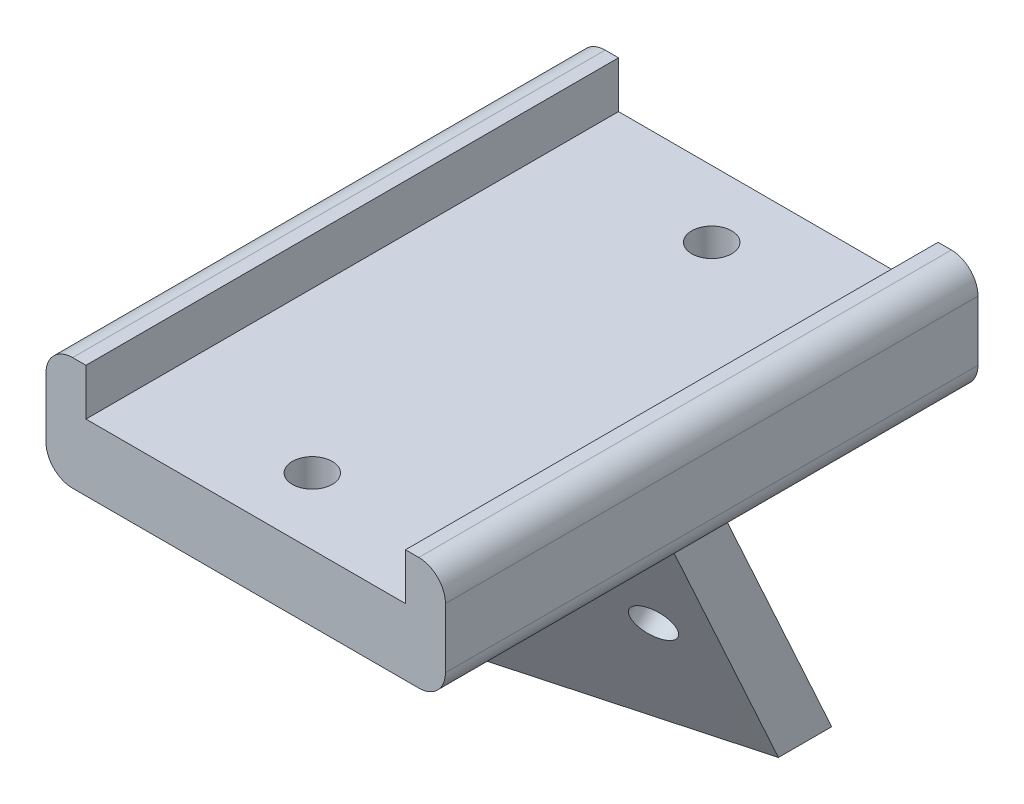
SolidWorks part; units mm, degrees
ref_plane "Front Plane" through (0, 0, 0) normal (0, 0, 1) x (1, 0, 0)
ref_plane "Top Plane" through (0, 0, 0) normal (0, 1, 0) x (1, 0, 0)
ref_plane "Right Plane" through (0, 0, 0) normal (1, 0, 0) x (0, 0, -1)
sketch "Sketch1" plane through (0, 0, 0) normal (0, 1, 0) x (1, 0, 0)
  line L1 (-11, -20) -> (11, -20)
  line L2 (-11, -20) -> (-11, 20)
  line L3 (-11, 20) -> (11, 20)
  line L4 (11, -20) -> (11, 20)
  line L5 (-11, -20) -> (11, 20) construction
  line L6 (-11, 20) -> (11, -20) construction
  circle A0 centre (0, 15) radius 1.5
  circle A1 centre (0, -15) radius 1.5
  point P0 (0, 0)
  dimension "D1" = 30
  dimension "D2" = 15
  dimension "D3" = 3
  dimension "D4" = 3
  dimension "D5" = 40
  dimension "D6" = 22
extrude "Boss-Extrude1" add sketch "Sketch1" along normal blind 5
sketch "Sketch2" plane through (0, 0, 0) normal (0, -1, 0) x (1, 0, 0)
  line L0 (-11, 6) -> (11, 0.1051)
  line L1 (-11, -20) -> (-11, 20) construction
  line L2 (11, 20) -> (11, -20) construction
  line L3 (11, 0.1051) -> (11, -3.8949)
  line L4 (11, -3.8949) -> (-11, 2)
  line L5 (-11, 2) -> (-11, 6)
  dimension "D1" = 4
  dimension "D2" = 4
  dimension "D3" = 105
  dimension "D4" = 14
sketch "Sketch4" plane through (0, 0, -20) normal (0, 0, -1) x (-1, 0, 0)
  line L0 (-11, 5) -> (-12, 5)
  line L1 (-12, 5) -> (-12, 8.5)
  line L2 (-12, 8.5) -> (-15, 8.5)
  line L3 (-15, 8.5) -> (-15, 0)
  line L4 (-15, 0) -> (-11, 0)
  line L5 (-11, 0) -> (-11, 5)
  line L6 (0, 0) -> (0, 5) construction
  line L7 (-11, 0) -> (11, 0) construction
  line L8 (-11, 5) -> (11, 5) construction
  line L9 (11, 0) -> (11, 5)
  line L10 (15, 0) -> (11, 0)
  line L11 (15, 8.5) -> (15, 0)
  line L12 (12, 8.5) -> (15, 8.5)
  line L13 (12, 5) -> (12, 8.5)
  line L14 (11, 5) -> (12, 5)
  dimension "D1" = 1
  dimension "D2" = 3
  dimension "D3" = 3.5
extrude "Boss-Extrude3" add sketch "Sketch4" against normal up to surface (40 mm away) up to face at (0, 2.5, 20)
fillet "Fillet1" radius 2 4 edges at (15, 0, 0) (15, 8.5, 0) (-15, 0, 0) (-15, 8.5, 0)
ref_plane "Plane1" through (0, -20, 0) normal (0, 1, 0) x (1, 0, 0)
sketch "Sketch6" plane through (0, -20, 0) normal (0, 1, 0) x (1, 0, 0)
  line L0 (11.018, 12.9927) -> (-11, 7)
  line L1 (-11, 7) -> (-11, 3)
  line L2 (-11, 3) -> (11.018, 8.9927)
  line L3 (11.018, 8.9927) -> (11.018, 12.9927)
  line L4 (-13, -20) -> (-13, 20) construction
  line L5 (-13, -20) -> (13, -20) construction
  dimension "D1" = 2
  dimension "D2" = 4
  dimension "D3" = 4
  dimension "D4" = 23
loft "Loft1" add profiles "Sketch6", "Sketch2"
ref_plane "Plane3" through (-0.1915, 0.3198, -0.7035) normal (-0.2405, 0.4017, -0.8836) x (-0.9707, -0.0995, 0.2189)
sketch "Sketch9" plane through (-0.1915, 0.3198, -0.7035) normal (-0.2405, 0.4017, -0.8836) x (-0.9707, -0.0995, 0.2189)
  line L1 (-11.5484, -23.584) -> (-11.5299, -1.612) construction
  line L2 (11.115, 0.8278) -> (-11.5299, -1.612) construction
  line L3 (11.1354, -21.1038) -> (11.115, 0.8278) construction
  circle A0 centre (-6.5379, -11.132) radius 1.5
  circle A1 centre (6.1248, -9.7678) radius 1.5
  dimension "D1" = 5
  dimension "D2" = 10
  dimension "D3" = 5
  dimension "D4" = 10
  dimension "D5" = 3
  dimension "D6" = 3
extrude "Cut-Extrude1" cut sketch "Sketch9" against normal up to surface and the other way up to surface up to face at (0.0045, -15, -3.7219) other way up to face at (0.009, -15, -7.7464)
